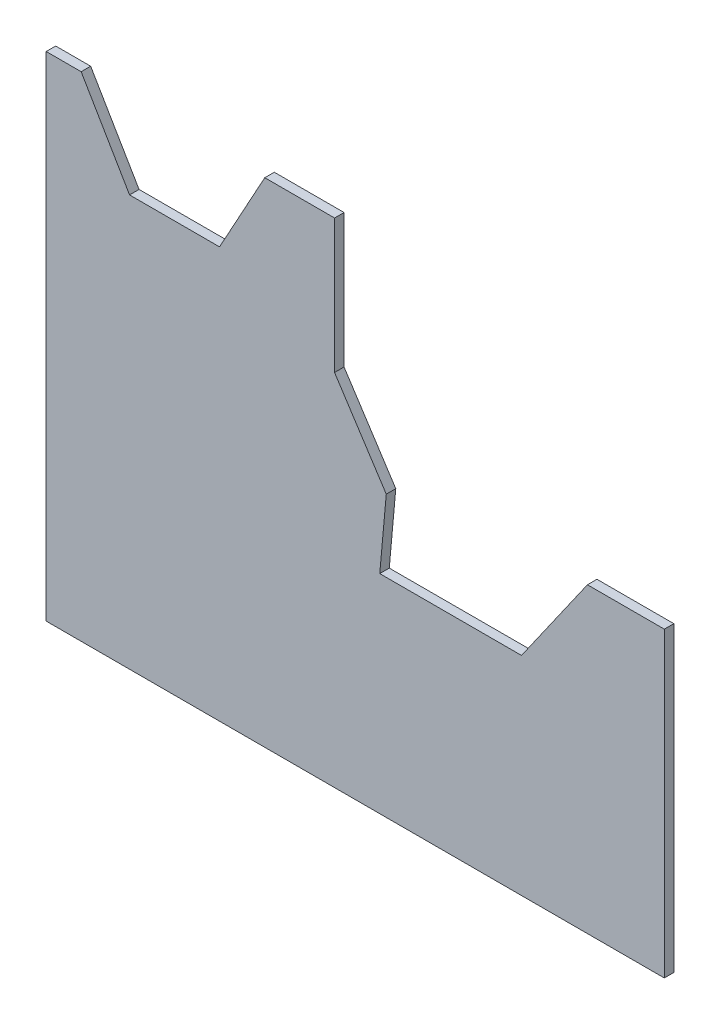
SolidWorks part; units mm, degrees
ref_plane "Front Plane" through (0, 0, 0) normal (0, 0, 1) x (1, 0, 0)
ref_plane "Top Plane" through (0, 0, 0) normal (0, 1, 0) x (1, 0, 0)
ref_plane "Right Plane" through (0, 0, 0) normal (1, 0, 0) x (0, 0, -1)
sketch "Sketch1" plane through (0, 0, 0) normal (0, 0, 1) x (1, 0, 0)
  line L0 (11.2798, -8.083) -> (4.813, -8.083)
  line L2 (-40.7202, 8.0008) -> (-40.7202, -33.5)
  line L3 (-40.7202, -33.5) -> (11.2798, -33.5)
  line L4 (11.2798, -8.083) -> (11.2798, -33.5)
  line L5 (4.813, -8.083) -> (-0.7348, -16.006)
  line L6 (-0.7348, -16.006) -> (-12.6577, -16.006)
  line L7 (-12.6577, -16.006) -> (-12.1107, -9.9448)
  line L8 (-12.1107, -9.9448) -> (-16.4603, -3.2544)
  line L9 (-16.4603, -3.2544) -> (-16.4603, 8.0008)
  line L10 (-16.4603, 8.0008) -> (-22.3305, 8.0008)
  line L11 (-22.3305, 8.0008) -> (-26.1366, 1.0586)
  line L12 (-26.1366, 1.0586) -> (-33.707, 1.0586)
  line L13 (-33.707, 1.0586) -> (-37.7788, 8.0008)
  line L14 (-37.7788, 8.0008) -> (-40.7202, 8.0008)
  point P0 (-12.0577, -9.9766)
  point P6 (-44.1094, 8.3493)
  dimension "D1" = 52
  dimension "D2" = 125
extrude "Boss-Extrude1" add sketch "Sketch1" along normal blind 0.8
